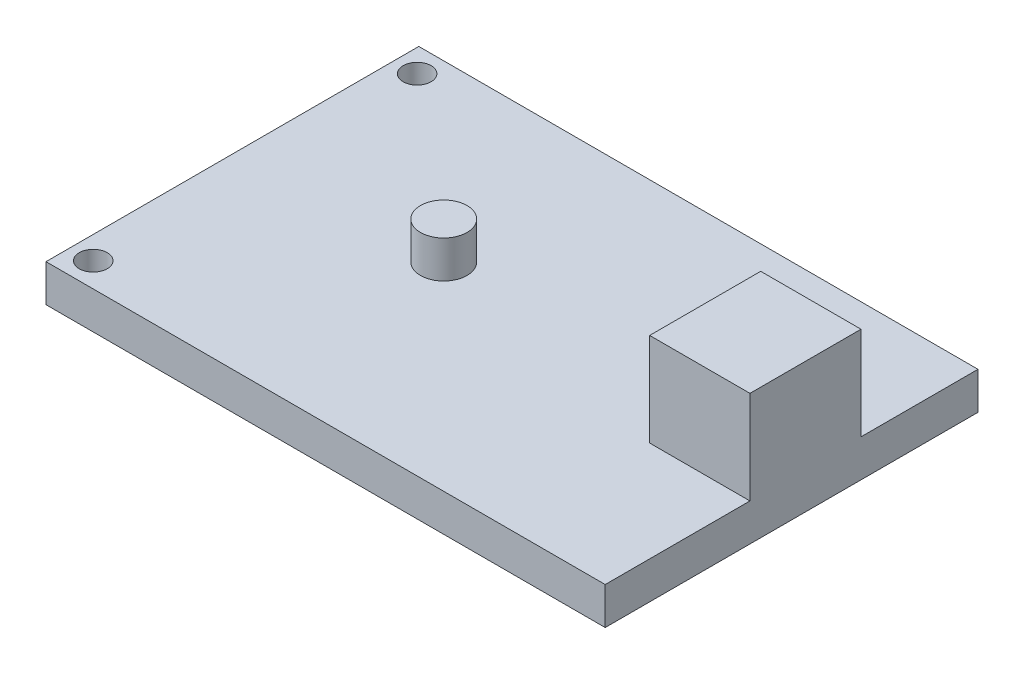
SolidWorks part; units mm, degrees
ref_plane "Plan de face" through (0, 0, 0) normal (0, 0, 1) x (1, 0, 0)
ref_plane "Plan de dessus" through (0, 0, 0) normal (0, 1, 0) x (1, 0, 0)
ref_plane "Plan de droite" through (0, 0, 0) normal (1, 0, 0) x (0, 0, -1)
sketch "Esquisse1" plane through (0, 0, 0) normal (0, 1, 0) x (1, 0, 0)
  line L1 (-15, 10) -> (15, 10)
  line L2 (-15, 10) -> (-15, -10)
  line L3 (-15, -10) -> (15, -10)
  line L4 (15, 10) -> (15, -10)
  line L5 (-15, 10) -> (15, -10) construction
  line L6 (-15, -10) -> (15, 10) construction
  point P0 (0, 0)
  dimension "D1" = 30
  dimension "D2" = 20
extrude "Boss.-Extru.1" add sketch "Esquisse1" along normal blind 2
sketch "Esquisse2" plane through (0, 2, 0) normal (0, 1, 0) x (1, 0, 0)
  circle A0 centre (-13.7772, -8.6884) radius 0.75
  dimension "D1" = 1.5
extrude "Enlèv. mat.-Extru.1" cut sketch "Esquisse2" against normal blind 2
mirror "Symétrie1" about plane through (0, 0, 0) normal (0, 0, 1) of "Enlèv. mat.-Extru.1"
sketch "Esquisse3" plane through (0, 2, 0) normal (0, 1, 0) x (1, 0, 0)
  circle A0 centre (-4.3131, 0.6516) radius 1.25
  dimension "D1" = 2.5
extrude "Boss.-Extru.2" add sketch "Esquisse3" along normal blind 2
sketch "Esquisse4" plane through (0, 2, 0) normal (0, 1, 0) x (1, 0, 0)
  line L0 (15, -10) -> (15, 10) construction
  line L1 (15, 3.7236) -> (9.6192, 3.7236)
  line L2 (15, 3.7236) -> (15, -2.2341)
  line L3 (15, -2.2341) -> (9.6192, -2.2341)
  line L4 (9.6192, 3.7236) -> (9.6192, -2.2341)
extrude "Boss.-Extru.3" add sketch "Esquisse4" along normal blind 5
